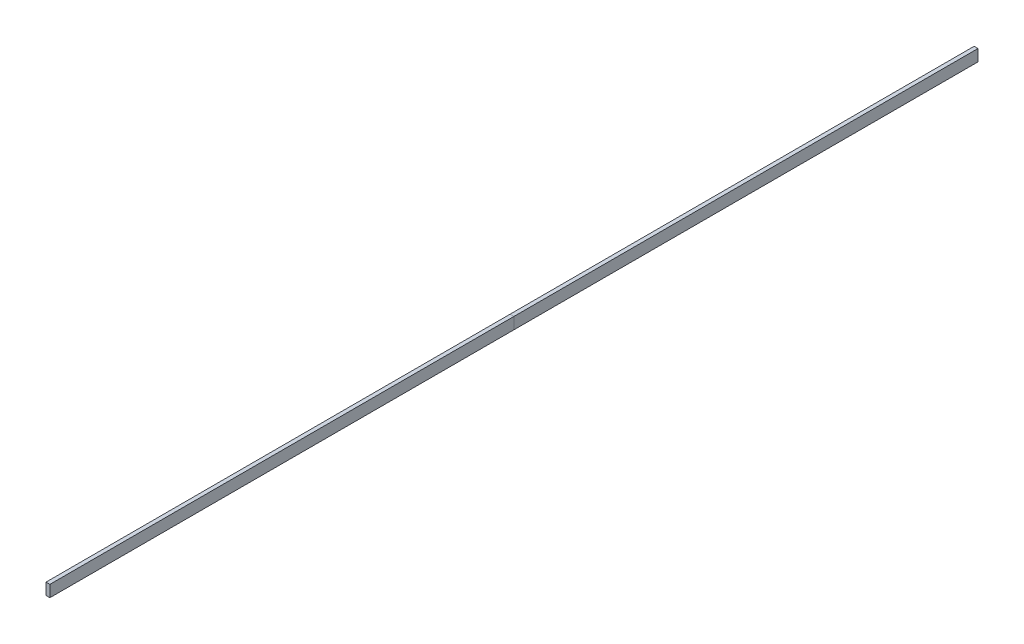
SolidWorks part; units mm, degrees
ref_plane "Front Plane" through (0, 0, 0) normal (0, 0, 1) x (1, 0, 0)
ref_plane "Top Plane" through (0, 0, 0) normal (0, 1, 0) x (1, 0, 0)
ref_plane "Right Plane" through (0, 0, 0) normal (1, 0, 0) x (0, 0, -1)
other "Configuration Table"
sketch "Sketch1" plane through (0, 0, 0) normal (0, 0, 1) x (1, 0, 0)
  line L1 (-12.7, -38.1) -> (12.7, -38.1)
  line L2 (-12.7, -38.1) -> (-12.7, 38.1)
  line L3 (-12.7, 38.1) -> (12.7, 38.1)
  line L4 (12.7, -38.1) -> (12.7, 38.1)
  line L5 (-12.7, -38.1) -> (12.7, 38.1) construction
  line L6 (-12.7, 38.1) -> (12.7, -38.1) construction
  point P0 (0, 0)
  dimension "D1" = 76.2
  dimension "D2" = 25.4
extrude "Extrude1" add sketch "Sketch1" along normal blind 3048
sketch "Sketch2" plane through (0, 0, 3048) normal (0, 0, 1) x (1, 0, 0)
  line L4 (12.7, -38.1) -> (12.7, 38.1)
  line L5 (12.7, 38.1) -> (-12.7, 38.1)
  line L6 (-12.7, 38.1) -> (-12.7, -38.1)
  line L7 (-12.7, -38.1) -> (12.7, -38.1)
  line L8 (12.7, -38.1) -> (12.7, 38.1)
  line L9 (12.7, 38.1) -> (-12.7, 38.1)
  line L10 (-12.7, 38.1) -> (-12.7, -38.1)
  line L11 (-12.7, -38.1) -> (12.7, -38.1)
  dimension "D1" = 0
extrude "Extrude2" add sketch "Sketch2" along normal blind 3048 separate body
sketch "Sketch3" plane through (0, 38.1, 0) normal (0, 1, 0) x (1, 0, 0)
  line L0 (-13.97, 0) -> (13.97, 0) construction
  point P0 (0, -1828.8)
  dimension "D1" = 1828.8
ref_point "Point1"
sketch "Sketch4" plane through (0, 38.1, 0) normal (0, 1, 0) x (1, 0, 0)
  line L1 (12.7, -3048) -> (-12.7, -3048) construction
  point P0 (0, -4572)
  point P1 (0, -3048)
  dimension "D1" = 1524
ref_point "Point2"
